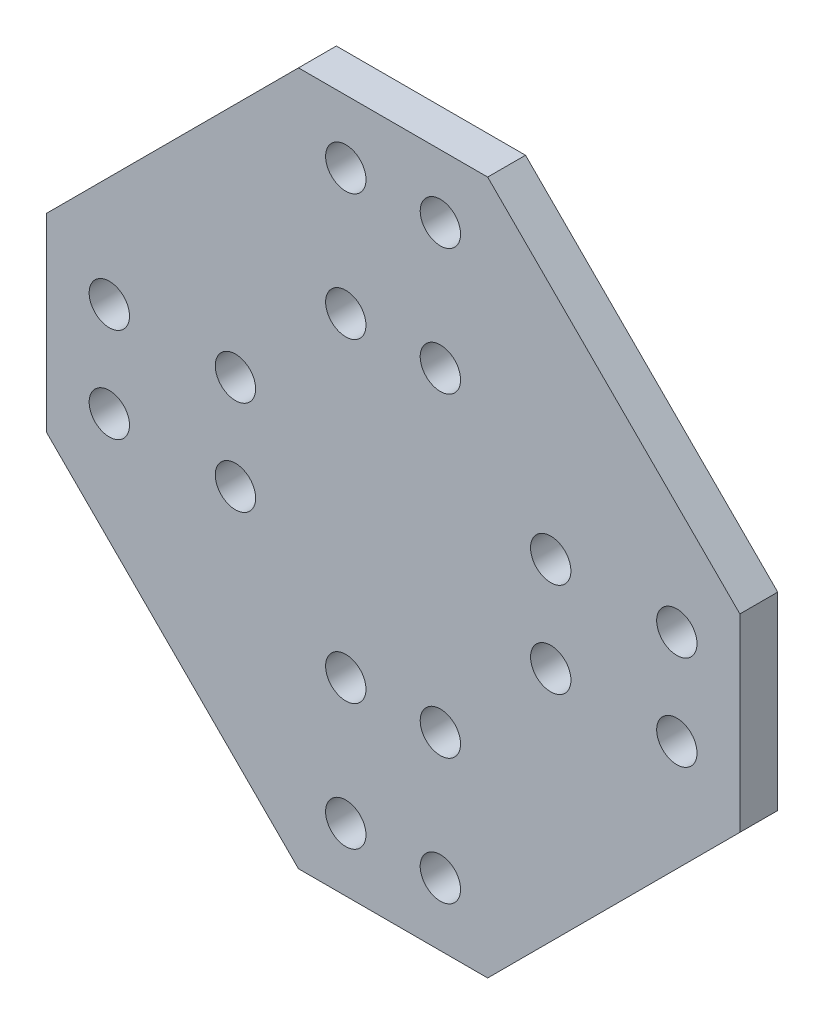
SolidWorks part; units mm, degrees
ref_plane "前视基准面" through (0, 0, 0) normal (0, 0, 1) x (1, 0, 0)
ref_plane "上视基准面" through (0, 0, 0) normal (0, 1, 0) x (1, 0, 0)
ref_plane "右视基准面" through (0, 0, 0) normal (1, 0, 0) x (0, 0, -1)
other "Configuration Table"
sketch "草图1" plane through (0, 0, 0) normal (0, 0, 1) x (1, 0, 0)
  line L0 (0, 0) -> (15, 0)
  line L1 (15, 0) -> (35, -20)
  line L2 (35, -20) -> (35, -35)
  line L3 (35, -35) -> (15, -55)
  line L4 (15, -55) -> (0, -55)
  line L5 (0, -55) -> (-20, -35)
  line L6 (-20, -35) -> (-20, -20)
  line L7 (-20, -20) -> (0, 0)
  line L8 (-20, -20) -> (35, -20) construction
  line L9 (-20, -35) -> (35, -35) construction
  line L10 (7.5, 0) -> (7.5, -55) construction
  point P11 (35.7526, -20)
  dimension "D1" = 15
  dimension "D2" = 15
  dimension "D3" = 15
  dimension "D4" = 55
  dimension "D5" = 20
extrude "凸台-拉伸1" add sketch "草图1" along normal blind 3
sketch "草图2" plane through (0, 0, 0) normal (0, 0, -1) x (-1, 0, 0)
  line L0 (-7.5, 0) -> (-7.5, -55) construction
  line L1 (-15, 0) -> (0, 0) construction
  line L2 (0, -55) -> (-15, -55) construction
  line L3 (-35, -27.5) -> (20, -27.5) construction
  line L4 (-35, -35) -> (-35, -20) construction
  line L5 (20, -20) -> (20, -35) construction
  line L6 (-25, -10) -> (10, -10) construction
  line L7 (-35, -20) -> (-15, 0) construction
  line L8 (0, 0) -> (20, -20) construction
  line L9 (-25, -10) -> (-25, -45) construction
  line L10 (-15, -55) -> (-35, -35) construction
  circle A0 centre (-11.25, -5) radius 1.6
  circle A1 centre (-30, -31.25) radius 1.6
  circle A2 centre (-30, -23.75) radius 1.6
  circle A3 centre (-3.75, -5) radius 1.6
  circle A4 centre (-3.75, -15) radius 1.6
  circle A5 centre (-11.25, -15) radius 1.6
  circle A6 centre (-20, -23.75) radius 1.6
  circle A7 centre (-20, -31.25) radius 1.6
  circle A8 centre (5, -31.25) radius 1.6
  circle A9 centre (5, -23.75) radius 1.6
  circle A10 centre (15, -23.75) radius 1.6
  circle A11 centre (15, -31.25) radius 1.6
  circle A12 centre (-11.25, -40) radius 1.6
  circle A13 centre (-3.75, -40) radius 1.6
  circle A14 centre (-3.75, -50) radius 1.6
  circle A15 centre (-11.25, -50) radius 1.6
  point P28 (-29.9937, -28.8)
  dimension "D3" = 3.2
  dimension "D6" = 3.2
  dimension "D7" = 3.75
  dimension "D1" = 10
  dimension "D2" = 10
  dimension "D4" = 3.75
  dimension "D5" = 5
  dimension "D8" = 5
extrude "切除-拉伸1" cut sketch "草图2" against normal through all
